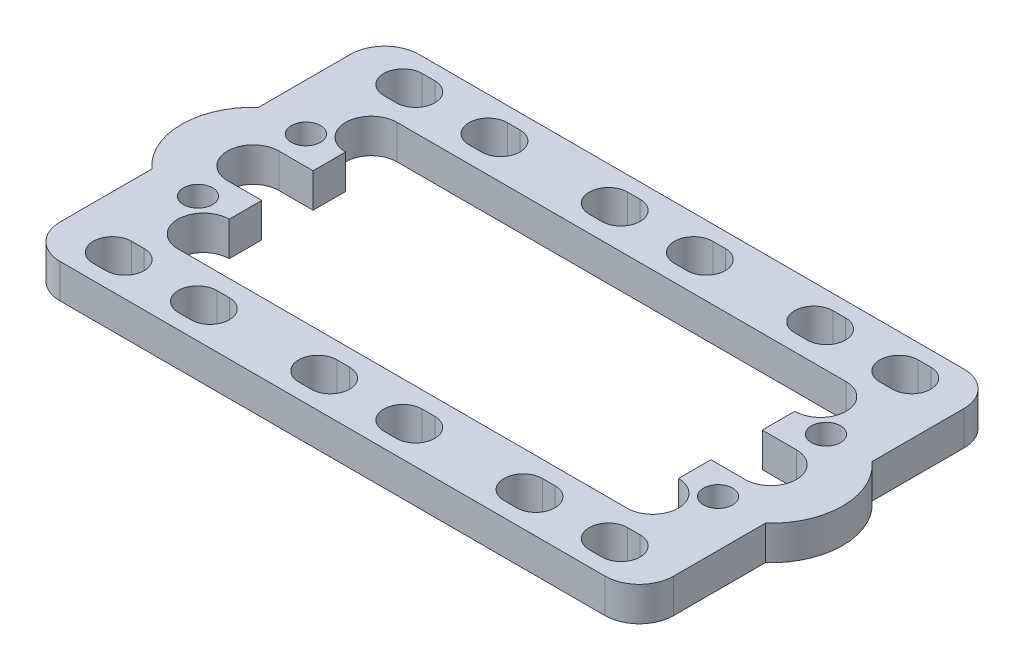
SolidWorks part; units mm, degrees
material "6061 Alloy"
ref_plane "Front Plane" through (0, 0, 0) normal (0, 0, 1) x (1, 0, 0)
ref_plane "Top Plane" through (0, 0, 0) normal (0, 1, 0) x (1, 0, 0)
ref_plane "Right Plane" through (0, 0, 0) normal (1, 0, 0) x (0, 0, -1)
sketch "Sketch1" plane through (0, 0, 0) normal (0, 1, 0) x (1, 0, 0)
  line L0 (28.448, 0) -> (28.448, 33.274) construction
  line L1 (3.175, 0) -> (53.721, 0)
  line L2 (0, 3.175) -> (0, 11.684)
  line L3 (3.175, 33.274) -> (53.721, 33.274)
  line L4 (56.896, 3.175) -> (56.896, 11.684)
  line L5 (28.448, 16.637) -> (0, 16.637) construction
  line L6 (49.276, 26.797) -> (7.62, 26.797)
  line L7 (7.62, 22.0345) -> (7.62, 19.0182)
  line L8 (7.62, 19.0182) -> (4.4459, 19.0182)
  line L9 (7.62, 14.2557) -> (4.4459, 14.2557)
  line L10 (7.62, 11.2395) -> (7.62, 14.2557)
  line L11 (49.276, 6.477) -> (7.62, 6.477)
  line L12 (49.276, 11.2395) -> (49.276, 14.2558)
  line L13 (49.276, 14.2558) -> (52.4501, 14.2557)
  line L14 (49.276, 19.0182) -> (52.4501, 19.0183)
  line L15 (49.276, 22.0345) -> (49.276, 19.0182)
  line L16 (0, 21.59) -> (0, 30.099)
  line L17 (56.896, 21.59) -> (56.896, 30.099)
  arc A0 (3.175, 0) -> (0, 3.175) centre (3.175, 3.175) cw
  arc A1 (53.721, 0) -> (56.896, 3.175) centre (53.721, 3.175) ccw
  arc A2 (53.721, 33.274) -> (56.896, 30.099) centre (53.721, 30.099) cw
  arc A3 (0, 30.099) -> (3.175, 33.274) centre (3.175, 30.099) cw
  arc A4 (0, 11.684) -> (0, 21.59) centre (4.4459, 16.637) cw
  arc A5 (7.62, 26.797) -> (7.62, 22.0345) centre (7.62, 24.4157) ccw
  arc A6 (4.4459, 19.0182) -> (4.4459, 14.2557) centre (4.4459, 16.637) ccw
  arc A7 (7.62, 6.477) -> (7.62, 11.2395) centre (7.62, 8.8582) cw
  arc A8 (49.276, 6.477) -> (49.276, 11.2395) centre (49.276, 8.8583) ccw
  arc A9 (52.4501, 19.0183) -> (52.4501, 14.2557) centre (52.4501, 16.637) cw
  arc A10 (49.276, 26.797) -> (49.276, 22.0345) centre (49.276, 24.4157) cw
  arc A11 (56.896, 11.684) -> (56.896, 21.59) centre (52.4501, 16.637) ccw
  point P7 (0, 0)
  point P10 (56.896, 0)
  point P13 (56.896, 33.274)
  point P23 (-2.2098, 16.637)
  point P37 (28.448, 6.477)
  point P47 (28.448, 26.797)
  dimension "D3" = 3.175
  dimension "D7" = 2.3813
  dimension "D1" = 56.896
  dimension "D2" = 33.274
  dimension "D4" = 61.3156
  dimension "D5" = 20.32
  dimension "D6" = 41.656
  dimension "D8" = 9.906
extrude "Boss-Extrude1" add sketch "Sketch1" along normal blind 3.175
hole_wizard "#6-32 Tapped Hole1" positions "Sketch3" profile "Sketch4" tap size "#6-32" standard "ANSI Inch" end condition up to next
sketch "Sketch3" plane through (0, 3.175, 0) normal (0, 1, 0) x (1, 0, 0)
  line L0 (28.448, 0) -> (28.448, 33.274) construction
  line L1 (3.175, 0) -> (53.721, 0) construction
  line L4 (53.721, 33.274) -> (3.175, 33.274) construction
  line L5 (28.448, 16.637) -> (0, 16.637) construction
  line L7 (0, 30.099) -> (0, 21.59) construction
  point P18 (4.3307, 21.6408)
  point P22 (4.3307, 11.6332)
  point P23 (52.5653, 11.6332)
  point P24 (52.5653, 21.6408)
  dimension "D1" = 48.2346
  dimension "D2" = 10.0076
sketch "Sketch4" plane through (4.3307, 3.175, -21.6408) normal (1, 0, 0) x (0, 0, 1)
  line L0 (0, 0) -> (0, 3.175)
  line L1 (0, 3.175) -> (1.3525, 3.175)
  line L2 (1.3525, 3.175) -> (1.3525, 0)
  line L5 (1.3525, 0) -> (0, 0)
  line L11 (0, -6.35) -> (0, 107.95) construction
  dimension "Thread Major Dia." = 2.7051
  dimension "Thru Tap Drill Depth" = 3.175
sketch "Sketch5" plane through (0, 3.175, 0) normal (0, 1, 0) x (1, 0, 0)
  line L0 (-2.2098, 16.637) -> (59.1058, 16.637) construction
  line L1 (28.448, 16.637) -> (28.448, 33.274) construction
  line L2 (53.721, 33.274) -> (3.175, 33.274) construction
  line L3 (28.448, 30.1117) -> (0, 30.1117) construction
  line L4 (23.9141, 30.1117) -> (25.0825, 30.1117) construction
  line L5 (23.9141, 31.8897) -> (25.0825, 31.8897)
  line L6 (23.9141, 28.3337) -> (25.0825, 28.3337)
  line L7 (12.7635, 30.1117) -> (13.9319, 30.1117) construction
  line L8 (12.7635, 31.8897) -> (13.9319, 31.8897)
  line L9 (12.7635, 28.3337) -> (13.9319, 28.3337)
  line L10 (0, 30.099) -> (0, 21.59) construction
  line L11 (4.8641, 30.1117) -> (6.0325, 30.1117) construction
  line L12 (4.8641, 31.8897) -> (6.0325, 31.8897)
  line L13 (4.8641, 28.3337) -> (6.0325, 28.3337)
  line L14 (32.9819, 30.1117) -> (31.8135, 30.1117) construction
  line L15 (32.9819, 31.8897) -> (31.8135, 31.8897)
  line L16 (32.9819, 28.3337) -> (31.8135, 28.3337)
  line L17 (44.1325, 30.1117) -> (42.9641, 30.1117) construction
  line L18 (44.1325, 31.8897) -> (42.9641, 31.8897)
  line L19 (44.1325, 28.3337) -> (42.9641, 28.3337)
  line L20 (52.0319, 30.1117) -> (50.8635, 30.1117) construction
  line L21 (52.0319, 31.8897) -> (50.8635, 31.8897)
  line L22 (52.0319, 28.3337) -> (50.8635, 28.3337)
  line L23 (52.0319, 3.1623) -> (50.8635, 3.1623) construction
  line L24 (52.0319, 1.3843) -> (50.8635, 1.3843)
  line L25 (52.0319, 4.9403) -> (50.8635, 4.9403)
  line L26 (44.1325, 3.1623) -> (42.9641, 3.1623) construction
  line L27 (44.1325, 1.3843) -> (42.9641, 1.3843)
  line L28 (44.1325, 4.9403) -> (42.9641, 4.9403)
  line L29 (32.9819, 3.1623) -> (31.8135, 3.1623) construction
  line L30 (32.9819, 1.3843) -> (31.8135, 1.3843)
  line L31 (32.9819, 4.9403) -> (31.8135, 4.9403)
  line L32 (23.9141, 3.1623) -> (25.0825, 3.1623) construction
  line L33 (23.9141, 1.3843) -> (25.0825, 1.3843)
  line L34 (23.9141, 4.9403) -> (25.0825, 4.9403)
  line L35 (12.7635, 3.1623) -> (13.9319, 3.1623) construction
  line L36 (12.7635, 1.3843) -> (13.9319, 1.3843)
  line L37 (12.7635, 4.9403) -> (13.9319, 4.9403)
  line L38 (4.8641, 3.1623) -> (6.0325, 3.1623) construction
  line L39 (4.8641, 1.3843) -> (6.0325, 1.3843)
  line L40 (4.8641, 4.9403) -> (6.0325, 4.9403)
  arc A0 (0, 21.59) -> (0, 11.684) centre (4.4459, 16.637) ccw construction
  arc A1 (56.896, 11.684) -> (56.896, 21.59) centre (52.4501, 16.637) ccw construction
  arc A2 (23.9141, 31.8897) -> (23.9141, 28.3337) centre (23.9141, 30.1117) ccw
  arc A3 (25.0825, 28.3337) -> (25.0825, 31.8897) centre (25.0825, 30.1117) ccw
  arc A4 (12.7635, 31.8897) -> (12.7635, 28.3337) centre (12.7635, 30.1117) ccw
  arc A5 (13.9319, 28.3337) -> (13.9319, 31.8897) centre (13.9319, 30.1117) ccw
  arc A6 (4.8641, 31.8897) -> (4.8641, 28.3337) centre (4.8641, 30.1117) ccw
  arc A7 (6.0325, 28.3337) -> (6.0325, 31.8897) centre (6.0325, 30.1117) ccw
  arc A8 (32.9819, 31.8897) -> (32.9819, 28.3337) centre (32.9819, 30.1117) cw
  arc A9 (31.8135, 28.3337) -> (31.8135, 31.8897) centre (31.8135, 30.1117) cw
  arc A10 (44.1325, 31.8897) -> (44.1325, 28.3337) centre (44.1325, 30.1117) cw
  arc A11 (42.9641, 28.3337) -> (42.9641, 31.8897) centre (42.9641, 30.1117) cw
  arc A12 (52.0319, 31.8897) -> (52.0319, 28.3337) centre (52.0319, 30.1117) cw
  arc A13 (50.8635, 28.3337) -> (50.8635, 31.8897) centre (50.8635, 30.1117) cw
  arc A14 (52.0319, 1.3843) -> (52.0319, 4.9403) centre (52.0319, 3.1623) ccw
  arc A15 (50.8635, 4.9403) -> (50.8635, 1.3843) centre (50.8635, 3.1623) ccw
  arc A16 (44.1325, 1.3843) -> (44.1325, 4.9403) centre (44.1325, 3.1623) ccw
  arc A17 (42.9641, 4.9403) -> (42.9641, 1.3843) centre (42.9641, 3.1623) ccw
  arc A18 (32.9819, 1.3843) -> (32.9819, 4.9403) centre (32.9819, 3.1623) ccw
  arc A19 (31.8135, 4.9403) -> (31.8135, 1.3843) centre (31.8135, 3.1623) ccw
  arc A20 (23.9141, 1.3843) -> (23.9141, 4.9403) centre (23.9141, 3.1623) cw
  arc A21 (25.0825, 4.9403) -> (25.0825, 1.3843) centre (25.0825, 3.1623) cw
  arc A22 (12.7635, 1.3843) -> (12.7635, 4.9403) centre (12.7635, 3.1623) cw
  arc A23 (13.9319, 4.9403) -> (13.9319, 1.3843) centre (13.9319, 3.1623) cw
  arc A24 (4.8641, 1.3843) -> (4.8641, 4.9403) centre (4.8641, 3.1623) cw
  arc A25 (6.0325, 4.9403) -> (6.0325, 1.3843) centre (6.0325, 3.1623) cw
  point P16 (24.4983, 30.1117)
  point P23 (13.3477, 30.1117)
  point P32 (5.4483, 30.1117)
  point P37 (7.8105, 30.1117)
  point P38 (10.9855, 30.1117)
  point P41 (32.3977, 30.1117)
  point P48 (43.5483, 30.1117)
  point P55 (51.4477, 30.1117)
  point P62 (51.4477, 3.1623)
  point P69 (43.5483, 3.1623)
  point P76 (32.3977, 3.1623)
  point P83 (24.4983, 3.1623)
  point P90 (13.3477, 3.1623)
  point P97 (5.4483, 3.1623)
  dimension "D2" = 1.778
  dimension "D1" = 26.9494
  dimension "D3" = 7.8994
  dimension "D4" = 7.8994
  dimension "D5" = 11.1506
  dimension "D6" = 3.175
extrude "Cut-Extrude1" cut sketch "Sketch5" against normal up to next
